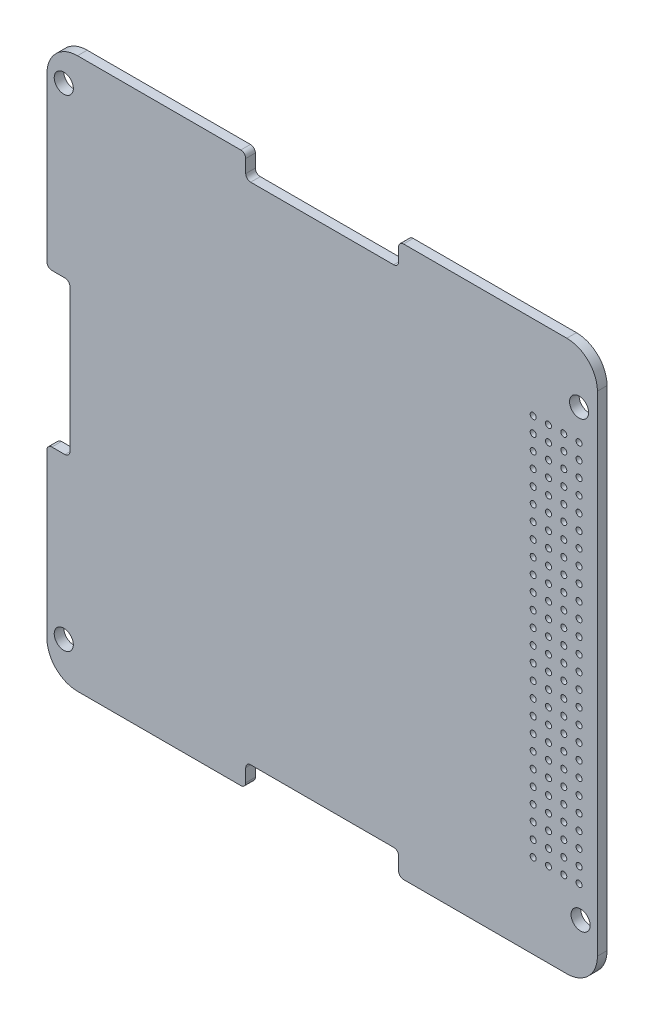
SolidWorks part; units mm, degrees
ref_plane "Front Plane" through (0, 0, 0) normal (0, 0, 1) x (1, 0, 0)
ref_plane "Top Plane" through (0, 0, 0) normal (0, 1, 0) x (1, 0, 0)
ref_plane "Right Plane" through (0, 0, 0) normal (1, 0, 0) x (0, 0, -1)
sketch "Sketch1" plane through (0, 0, 0) normal (0, 0, 1) x (1, 0, 0)
  line L0 (5.08, 0) -> (32.2024, 0)
  line L1 (33.02, 0.8176) -> (33.02, 2.9924)
  line L2 (33.8376, 3.81) -> (57.6024, 3.81)
  line L3 (58.42, 2.9924) -> (58.42, 0.8176)
  line L4 (59.2376, 0) -> (86.36, 0)
  line L5 (91.44, 5.08) -> (91.44, 86.36)
  line L6 (86.36, 91.44) -> (59.2376, 91.44)
  line L7 (58.42, 90.6224) -> (58.42, 88.4476)
  line L8 (57.6024, 87.63) -> (33.8376, 87.63)
  line L9 (33.02, 88.4476) -> (33.02, 90.6224)
  line L10 (32.2024, 91.44) -> (5.08, 91.44)
  line L11 (0, 86.36) -> (0, 59.2376)
  line L12 (0.8176, 58.42) -> (2.9924, 58.42)
  line L13 (3.81, 57.6024) -> (3.81, 33.8376)
  line L14 (2.9924, 33.02) -> (0.8176, 33.02)
  line L15 (0, 32.2024) -> (0, 5.08)
  arc A0 (5.08, 0) -> (0, 5.08) centre (5.08, 5.08) cw
  arc A1 (86.36, 0) -> (91.44, 5.08) centre (86.36, 5.08) ccw
  arc A2 (91.44, 86.36) -> (86.36, 91.44) centre (86.36, 86.36) ccw
  arc A3 (5.08, 91.44) -> (0, 86.36) centre (5.08, 86.36) ccw
  arc A4 (58.42, 0.8176) -> (59.2376, 0) centre (59.2376, 0.8176) ccw
  arc A5 (57.6024, 3.81) -> (58.42, 2.9924) centre (57.6024, 2.9924) cw
  arc A6 (33.02, 2.9924) -> (33.8376, 3.81) centre (33.8376, 2.9924) cw
  arc A7 (32.2024, 0) -> (33.02, 0.8176) centre (32.2024, 0.8176) ccw
  arc A8 (0.8176, 33.02) -> (0, 32.2024) centre (0.8176, 32.2024) ccw
  arc A9 (3.81, 33.8376) -> (2.9924, 33.02) centre (2.9924, 33.8376) cw
  arc A10 (2.9924, 58.42) -> (3.81, 57.6024) centre (2.9924, 57.6024) cw
  arc A11 (0, 59.2376) -> (0.8176, 58.42) centre (0.8176, 59.2376) ccw
  arc A12 (33.02, 90.6224) -> (32.2024, 91.44) centre (32.2024, 90.6224) ccw
  arc A13 (33.8376, 87.63) -> (33.02, 88.4476) centre (33.8376, 88.4476) cw
  arc A14 (58.42, 88.4476) -> (57.6024, 87.63) centre (57.6024, 88.4476) cw
  arc A15 (59.2376, 91.44) -> (58.42, 90.6224) centre (59.2376, 90.6224) ccw
  circle A16 centre (80.772, 77.47) radius 0.5
  circle A17 centre (83.312, 77.47) radius 0.5
  circle A18 centre (85.852, 77.47) radius 0.5
  circle A19 centre (88.392, 77.47) radius 0.5
  circle A20 centre (83.312, 74.93) radius 0.5
  circle A21 centre (85.852, 74.93) radius 0.5
  circle A22 centre (88.392, 74.93) radius 0.5
  circle A23 centre (83.312, 72.39) radius 0.5
  circle A24 centre (85.852, 72.39) radius 0.5
  circle A25 centre (88.392, 72.39) radius 0.5
  circle A26 centre (83.312, 69.85) radius 0.5
  circle A27 centre (85.852, 69.85) radius 0.5
  circle A28 centre (88.392, 69.85) radius 0.5
  circle A29 centre (83.312, 67.31) radius 0.5
  circle A30 centre (85.852, 67.31) radius 0.5
  circle A31 centre (88.392, 67.31) radius 0.5
  circle A32 centre (83.312, 64.77) radius 0.5
  circle A33 centre (85.852, 64.77) radius 0.5
  circle A34 centre (88.392, 64.77) radius 0.5
  circle A35 centre (83.312, 62.23) radius 0.5
  circle A36 centre (85.852, 62.23) radius 0.5
  circle A37 centre (88.392, 62.23) radius 0.5
  circle A38 centre (83.312, 59.69) radius 0.5
  circle A39 centre (85.852, 59.69) radius 0.5
  circle A40 centre (88.392, 59.69) radius 0.5
  circle A41 centre (83.312, 57.15) radius 0.5
  circle A42 centre (85.852, 57.15) radius 0.5
  circle A43 centre (88.392, 57.15) radius 0.5
  circle A44 centre (83.312, 54.61) radius 0.5
  circle A45 centre (85.852, 54.61) radius 0.5
  circle A46 centre (88.392, 54.61) radius 0.5
  circle A47 centre (83.312, 52.07) radius 0.5
  circle A48 centre (85.852, 52.07) radius 0.5
  circle A49 centre (88.392, 52.07) radius 0.5
  circle A50 centre (83.312, 49.53) radius 0.5
  circle A51 centre (85.852, 49.53) radius 0.5
  circle A52 centre (88.392, 49.53) radius 0.5
  circle A53 centre (83.312, 46.99) radius 0.5
  circle A54 centre (85.852, 46.99) radius 0.5
  circle A55 centre (88.392, 46.99) radius 0.5
  circle A56 centre (83.312, 44.45) radius 0.5
  circle A57 centre (85.852, 44.45) radius 0.5
  circle A58 centre (88.392, 44.45) radius 0.5
  circle A59 centre (83.312, 41.91) radius 0.5
  circle A60 centre (85.852, 41.91) radius 0.5
  circle A61 centre (88.392, 41.91) radius 0.5
  circle A62 centre (83.312, 39.37) radius 0.5
  circle A63 centre (85.852, 39.37) radius 0.5
  circle A64 centre (88.392, 39.37) radius 0.5
  circle A65 centre (83.312, 36.83) radius 0.5
  circle A66 centre (85.852, 36.83) radius 0.5
  circle A67 centre (88.392, 36.83) radius 0.5
  circle A68 centre (83.312, 34.29) radius 0.5
  circle A69 centre (85.852, 34.29) radius 0.5
  circle A70 centre (88.392, 34.29) radius 0.5
  circle A71 centre (83.312, 31.75) radius 0.5
  circle A72 centre (85.852, 31.75) radius 0.5
  circle A73 centre (88.392, 31.75) radius 0.5
  circle A74 centre (83.312, 29.21) radius 0.5
  circle A75 centre (85.852, 29.21) radius 0.5
  circle A76 centre (88.392, 29.21) radius 0.5
  circle A77 centre (83.312, 26.67) radius 0.5
  circle A78 centre (85.852, 26.67) radius 0.5
  circle A79 centre (88.392, 26.67) radius 0.5
  circle A80 centre (83.312, 24.13) radius 0.5
  circle A81 centre (85.852, 24.13) radius 0.5
  circle A82 centre (88.392, 24.13) radius 0.5
  circle A83 centre (83.312, 21.59) radius 0.5
  circle A84 centre (85.852, 21.59) radius 0.5
  circle A85 centre (88.392, 21.59) radius 0.5
  circle A86 centre (83.312, 19.05) radius 0.5
  circle A87 centre (85.852, 19.05) radius 0.5
  circle A88 centre (88.392, 19.05) radius 0.5
  circle A89 centre (83.312, 16.51) radius 0.5
  circle A90 centre (85.852, 16.51) radius 0.5
  circle A91 centre (88.392, 16.51) radius 0.5
  circle A92 centre (83.312, 13.97) radius 0.5
  circle A93 centre (85.852, 13.97) radius 0.5
  circle A94 centre (88.392, 13.97) radius 0.5
  circle A95 centre (80.772, 74.93) radius 0.5
  circle A96 centre (80.772, 72.39) radius 0.5
  circle A97 centre (80.772, 69.85) radius 0.5
  circle A98 centre (80.772, 67.31) radius 0.5
  circle A99 centre (80.772, 64.77) radius 0.5
  circle A100 centre (80.772, 62.23) radius 0.5
  circle A101 centre (80.772, 59.69) radius 0.5
  circle A102 centre (80.772, 57.15) radius 0.5
  circle A103 centre (80.772, 54.61) radius 0.5
  circle A104 centre (80.772, 52.07) radius 0.5
  circle A105 centre (80.772, 49.53) radius 0.5
  circle A106 centre (80.772, 46.99) radius 0.5
  circle A107 centre (80.772, 44.45) radius 0.5
  circle A108 centre (80.772, 41.91) radius 0.5
  circle A109 centre (80.772, 39.37) radius 0.5
  circle A110 centre (80.772, 36.83) radius 0.5
  circle A111 centre (80.772, 34.29) radius 0.5
  circle A112 centre (80.772, 31.75) radius 0.5
  circle A113 centre (80.772, 29.21) radius 0.5
  circle A114 centre (80.772, 26.67) radius 0.5
  circle A115 centre (80.772, 24.13) radius 0.5
  circle A116 centre (80.772, 21.59) radius 0.5
  circle A117 centre (80.772, 19.05) radius 0.5
  circle A118 centre (80.772, 16.51) radius 0.5
  circle A119 centre (80.772, 13.97) radius 0.5
  circle A120 centre (88.646, 8.89) radius 1.5875
  circle A121 centre (88.392, 82.55) radius 1.5875
  circle A123 centre (2.794, 6.35) radius 1.5875
  circle A124 centre (2.794, 86.36) radius 1.5875
  point P20 (0, 0)
  dimension "D7" = 5.08
  dimension "D8" = 0.8176
  dimension "D9" = 1
  dimension "D12" = 80.01
  dimension "D18" = 3.175
  dimension "D19" = 3.81
  dimension "D1" = 91.44
  dimension "D2" = 91.44
  dimension "D3" = 33.02
  dimension "D4" = 3.81
  dimension "D5" = 3.81
  dimension "D6" = 3.81
  dimension "D13" = 73.66
  dimension "D14" = 5.08
  dimension "D15" = 13.97
  dimension "D16" = 85.598
  dimension "D17" = 85.852
  dimension "D20" = 2.794
  dimension "D10" = 4
  dimension "D11" = 26
extrude "Boss-Extrude2" add sketch "Sketch1" along normal blind 1.6
